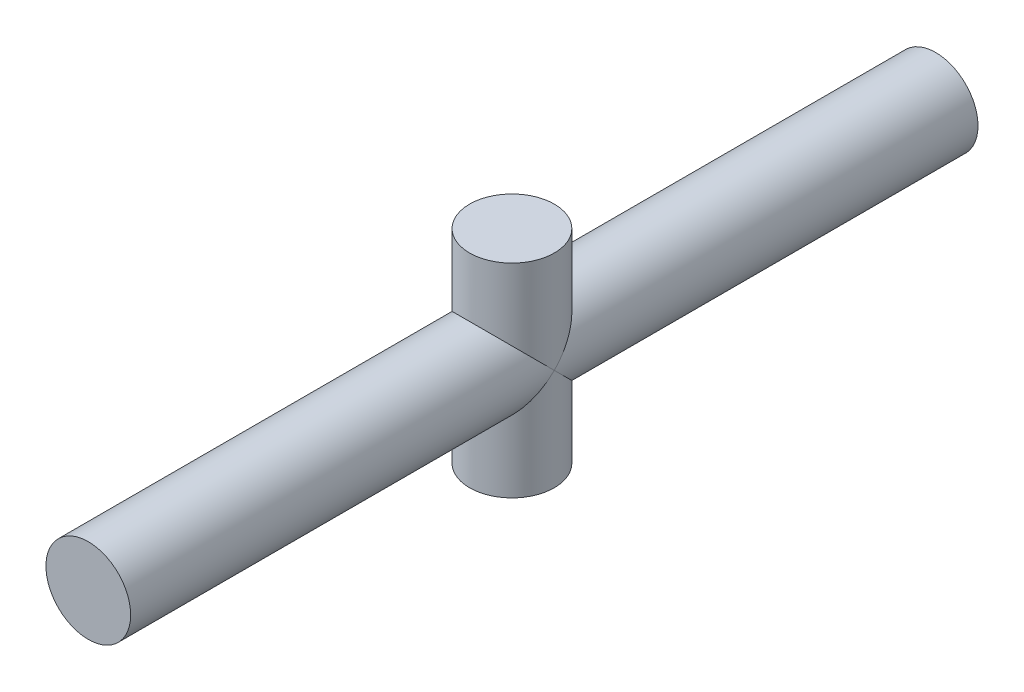
SolidWorks part; units mm, degrees
ref_plane "Front Plane" through (0, 0, 0) normal (0, 0, 1) x (1, 0, 0)
ref_plane "Top Plane" through (0, 0, 0) normal (0, 1, 0) x (1, 0, 0)
ref_plane "Right Plane" through (0, 0, 0) normal (1, 0, 0) x (0, 0, -1)
sketch "Sketch1" plane through (0, 0, 0) normal (0, 1, 0) x (1, 0, 0)
  circle A0 centre (0, 0) radius 2.5
  dimension "D1" = 5
extrude "Boss-Extrude1" add sketch "Sketch1" along normal blind 12
ref_plane "Plane1" through (0, 0, 0) normal (0, 0, 1) x (1, 0, 0)
sketch "Sketch2" plane through (0, 0, 0) normal (0, 0, 1) x (1, 0, 0)
  line L0 (2.5, 12) -> (-2.5, 12) construction
  line L1 (-2.5, 12) -> (-2.5, 0) construction
  circle A0 centre (0, 6) radius 2.5
  dimension "D1" = 5
  dimension "D2" = 6
  dimension "D3" = 2.5
extrude "Boss-Extrude2" add sketch "Sketch2" along normal mid plane 50
